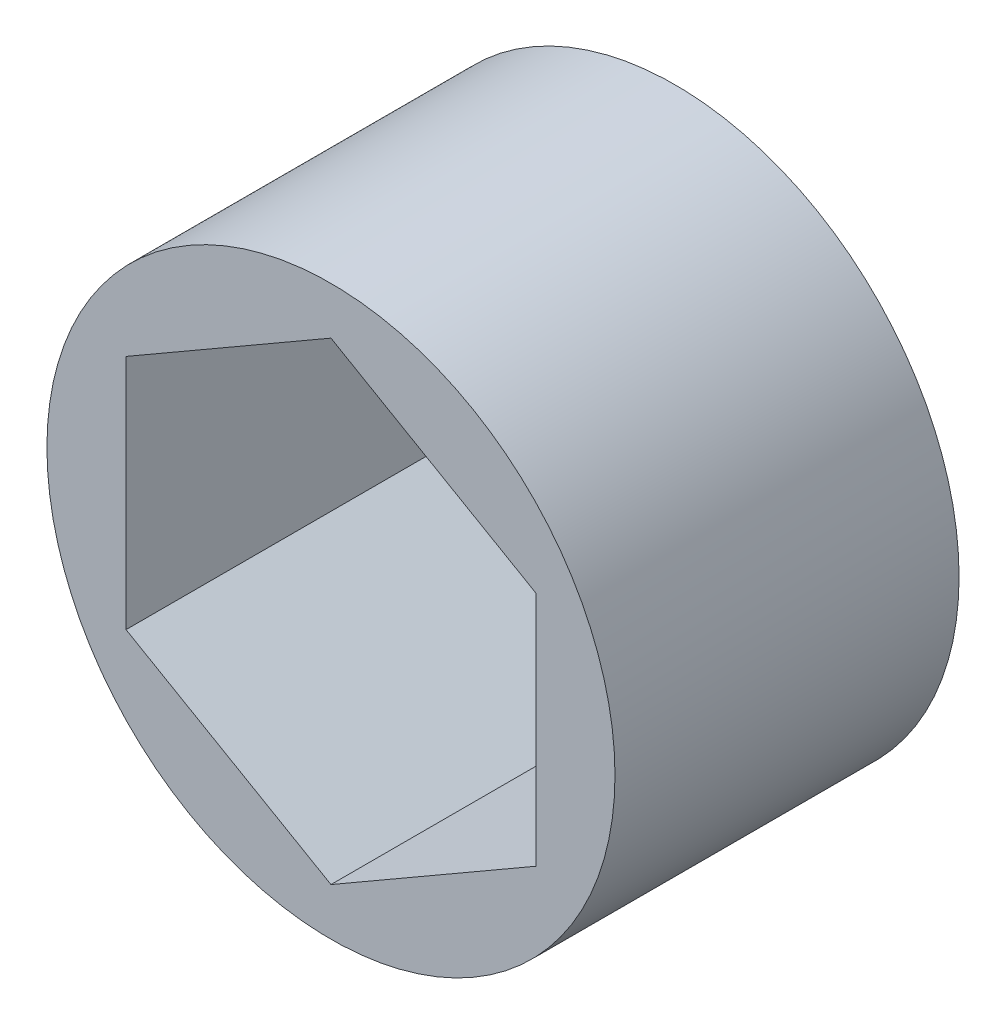
SolidWorks part; units mm, degrees
material "PET"
ref_plane "Front Plane" through (0, 0, 0) normal (0, 0, 1) x (1, 0, 0)
ref_plane "Top Plane" through (0, 0, 0) normal (0, 1, 0) x (1, 0, 0)
ref_plane "Right Plane" through (0, 0, 0) normal (1, 0, 0) x (0, 0, -1)
sketch "Sketch1" plane through (0, 0, 0) normal (0, 0, 1) x (1, 0, 0)
  line L1 (0, 7.4057) -> (-6.4135, 3.7028)
  line L2 (-6.4135, 3.7028) -> (-6.4135, -3.7028)
  line L3 (-6.4135, -3.7028) -> (0, -7.4057)
  line L4 (0, -7.4057) -> (6.4135, -3.7028)
  line L5 (6.4135, -3.7028) -> (6.4135, 3.7028)
  line L6 (6.4135, 3.7028) -> (0, 7.4057)
  circle A0 centre (0, 0) radius 6.4135 construction
  circle A1 centre (0, 0) radius 8.89
  dimension "D1" = 12.827
  dimension "D2" = 17.78
extrude "Boss-Extrude1" add sketch "Sketch1" along normal blind 10.7696
